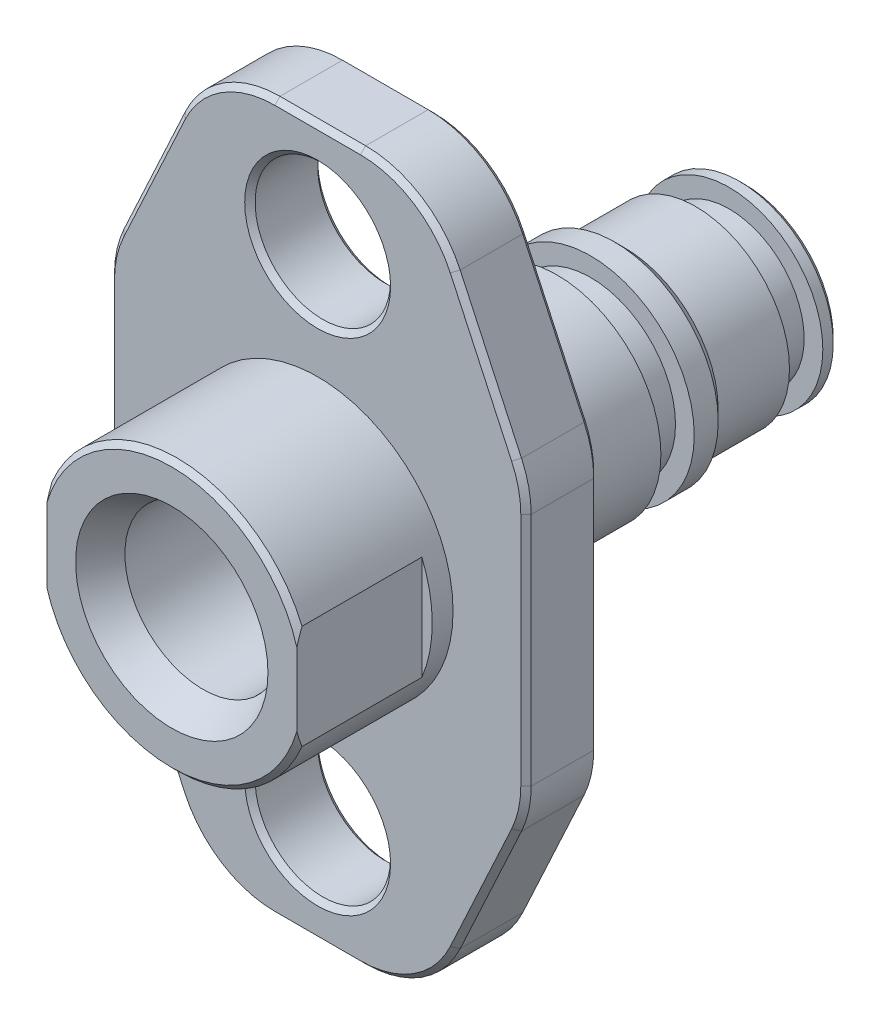
SolidWorks part; units mm, degrees
other "Markup1"
sketch "Sketch6" plane through (-20, -34, 0) normal (0, 0, 1) x (1, 0, 0)
material "316 S/Steel"
ref_plane "Front" through (0, 0, 0) normal (0, 0, 1) x (1, 0, 0)
ref_plane "Top" through (0, 0, 0) normal (0, 1, 0) x (1, 0, 0)
ref_plane "Right" through (0, 0, 0) normal (1, 0, 0) x (0, 0, -1)
sketch "Sketch1" plane through (0, 0, 0) normal (1, 0, 0) x (0, 0, -1)
  line L0 (0, 0) -> (55, 0) construction
  line L1 (14, 35) -> (21, 35)
  line L2 (0, 12.5) -> (0, 9.2321)
  line L3 (55, 4.75) -> (55, 8.49)
  line L4 (14, 35) -> (14, 13)
  line L5 (21, 35) -> (21, 9.95)
  line L6 (0.5, 13) -> (14, 13)
  line L7 (0, 35) -> (55, 35) construction
  line L8 (21, 9.95) -> (37, 9.95)
  line L9 (0, 35) -> (0, 0) construction
  line L10 (14, 35) -> (14, 0) construction
  line L11 (0, 13) -> (55, 13) construction
  line L12 (37, 8.15) -> (37, 9.95)
  line L13 (0, 9.95) -> (55, 9.95) construction
  line L14 (21, 35) -> (21, 0) construction
  line L15 (40.2, 8.15) -> (40.2, 9.95)
  line L16 (37, 8.15) -> (40.2, 8.15)
  line L17 (43.46, 8.99) -> (50.3, 8.99)
  line L18 (0, 8.15) -> (55, 8.15) construction
  line L19 (37, 0) -> (37, 9.95) construction
  line L20 (42.5, 9.95) -> (43.46, 8.99)
  line L21 (0, 8.99) -> (55, 8.99) construction
  line L22 (40.2, 9.95) -> (42.5, 9.95)
  line L23 (50.3, 7.2) -> (53.5, 7.2)
  line L24 (40.2, 0) -> (40.2, 9.95) construction
  line L25 (50.3, 7.2) -> (50.3, 8.99)
  line L26 (53.5, 7.2) -> (53.5, 8.99)
  line L27 (53.5, 8.99) -> (54.5, 8.99)
  line L28 (0, 7.2) -> (55, 7.2) construction
  line L29 (53.5, 0) -> (53.5, 9.95) construction
  line L30 (50.3, 0) -> (50.3, 9.95) construction
  line L31 (0, 12.5) -> (0.5, 13)
  line L32 (55, 0) -> (55, 9.95) construction
  line L33 (55, 8.49) -> (54.5, 8.99)
  line L34 (18.6524, 4.75) -> (55, 4.75)
  line L35 (17, 7.5) -> (18.6524, 4.75)
  line L36 (3, 7.5) -> (17, 7.5)
  line L37 (0, 4.75) -> (55, 4.75) construction
  line L38 (0, 9.2321) -> (3, 7.5)
  line L40 (0, 7.5) -> (55, 7.5) construction
  point P43 (17, 11.75)
  point P44 (17, 0)
  dimension "D1" = 55
  dimension "D2" = 35
  dimension "D3" = 14
  dimension "D4" = 7
  dimension "D5" = 34
  dimension "D6" = 13
  dimension "D7" = 9.95
  dimension "D8" = 12.5
  dimension "D9" = 45
  dimension "D10" = 8.15
  dimension "D11" = 18
  dimension "D12" = 3.2
  dimension "D13" = 8.99
  dimension "D14" = 1.5
  dimension "D15" = 3.2
  dimension "D16" = 7.2
  dimension "D17" = 0.5
  dimension "D18" = 45
  dimension "D19" = 45
  dimension "D20" = 0.5
  dimension "D21" = 17
  dimension "D22" = 7.5
  dimension "D23" = 4.75
  dimension "D24" = 59
  dimension "D25" = 30
  dimension "D26" = 3
revolve "Revolve1" add sketch "Sketch1" angle 360 about L0
cosmetic thread "Cosmetic Thread1" parameters "D2"=19.05
sketch "Sketch2" plane through (0, 0, 0) normal (0, 0, 1) x (1, 0, 0)
  line L0 (0, 0) -> (0, 34) construction
  line L1 (0, 0) -> (20, 0) construction
  line L2 (-4.1126, 34) -> (4.1126, 34)
  line L3 (20, -11.2955) -> (20, 11.2955)
  line L4 (19.0731, 15.5001) -> (13.1857, 28.2046)
  line L5 (19.0731, -15.5001) -> (13.1857, -28.2046)
  line L6 (0, 34) -> (20, 34) construction
  line L7 (20, 0) -> (20, 34) construction
  line L8 (-4.1126, -34) -> (4.1126, -34)
  line L9 (-19.0731, -15.5001) -> (-13.1857, -28.2046)
  line L10 (-19.0731, 15.5001) -> (-13.1857, 28.2046)
  line L11 (-20, -11.2955) -> (-20, 11.2955)
  arc A0 (19.0731, 15.5001) -> (20, 11.2955) centre (10, 11.2955) cw
  arc A1 (13.1857, 28.2046) -> (4.1126, 34) centre (4.1126, 24) ccw
  arc A2 (19.0731, -15.5001) -> (20, -11.2955) centre (10, -11.2955) ccw
  arc A3 (13.1857, -28.2046) -> (4.1126, -34) centre (4.1126, -24) cw
  arc A4 (-13.1857, -28.2046) -> (-4.1126, -34) centre (-4.1126, -24) ccw
  arc A5 (-19.0731, -15.5001) -> (-20, -11.2955) centre (-10, -11.2955) cw
  arc A6 (-13.1857, 28.2046) -> (-4.1126, 34) centre (-4.1126, 24) cw
  arc A7 (-19.0731, 15.5001) -> (-20, 11.2955) centre (-10, 11.2955) ccw
  circle A8 centre (0, 24) radius 6.5
  circle A9 centre (0, -24) radius 6.5
  point P9 (20, 13.5)
  point P12 (10.5, 34)
  point P19 (-10.5, 34)
  point P32 (0, -34)
  point P33 (-20, 13.5)
  dimension "D5" = 10
  dimension "D6" = 13
  dimension "D1" = 34
  dimension "D2" = 20
  dimension "D3" = 13.5
  dimension "D4" = 10.5
  dimension "D7" = 24
extrude "Cut-Extrude1" cut sketch "Sketch2" against normal blind 21 flip side to cut
sketch "Sketch5" plane through (0, 0, 0) normal (0, 0, 1) x (1, 0, 0)
  line L0 (0, 0) -> (-12, 0) construction
  line L2 (-12, 8.8472) -> (-14.0915, 8.8472)
  line L3 (-14.0915, 8.8472) -> (-14.0915, -9.1528)
  line L4 (-14.0915, -9.1528) -> (-12, -9.1528)
  line L6 (-12, 8.8472) -> (-12, -9.1528)
  dimension "D1" = 12
  dimension "D2" = 18
  dimension "D3" = 2.0915
extrude "Cut-Extrude2" cut sketch "Sketch5" against normal blind 12
pattern_circular "CirPattern1" count 2 over 180 about axis through (0, 0, -12) along (0, 1, 0) of "Cut-Extrude2"
chamfer "Chamfer1" distance 0.5 angle 45 36 edges at (-6.5, -24, -14) (-6.5, -24, -21) (-6.5, 24, -14) (6.5, 24, -21) (9.4956, -32.4275, -14) (0, -34, -14) (16.1294, -21.8524, -14) (-9.4956, -32.4275, -14) (19.7655, -13.4483, -14) (-16.1294, -21.8524, -14) (20, 0, -14) (-19.7655, -13.4483, -14) (19.7655, 13.4483, -14) (-20, 0, -14) (16.1294, 21.8524, -14) (-19.7655, 13.4483, -14) (9.4956, 32.4275, -14) (-16.1294, 21.8524, -14) (0, 34, -14) (-9.4956, 32.4275, -14) (-9.4956, -32.4275, -21) (0, -34, -21) (-16.1294, -21.8524, -21) (9.4956, -32.4275, -21) (-19.7655, -13.4483, -21) (16.1294, -21.8524, -21) (-20, 0, -21) (19.7655, -13.4483, -21) (-19.7655, 13.4483, -21) (20, 0, -21) (-16.1294, 21.8524, -21) (19.7655, 13.4483, -21) (-9.4956, 32.4275, -21) (16.1294, 21.8524, -21) (0, 34, -21) (9.4956, 32.4275, -21)
